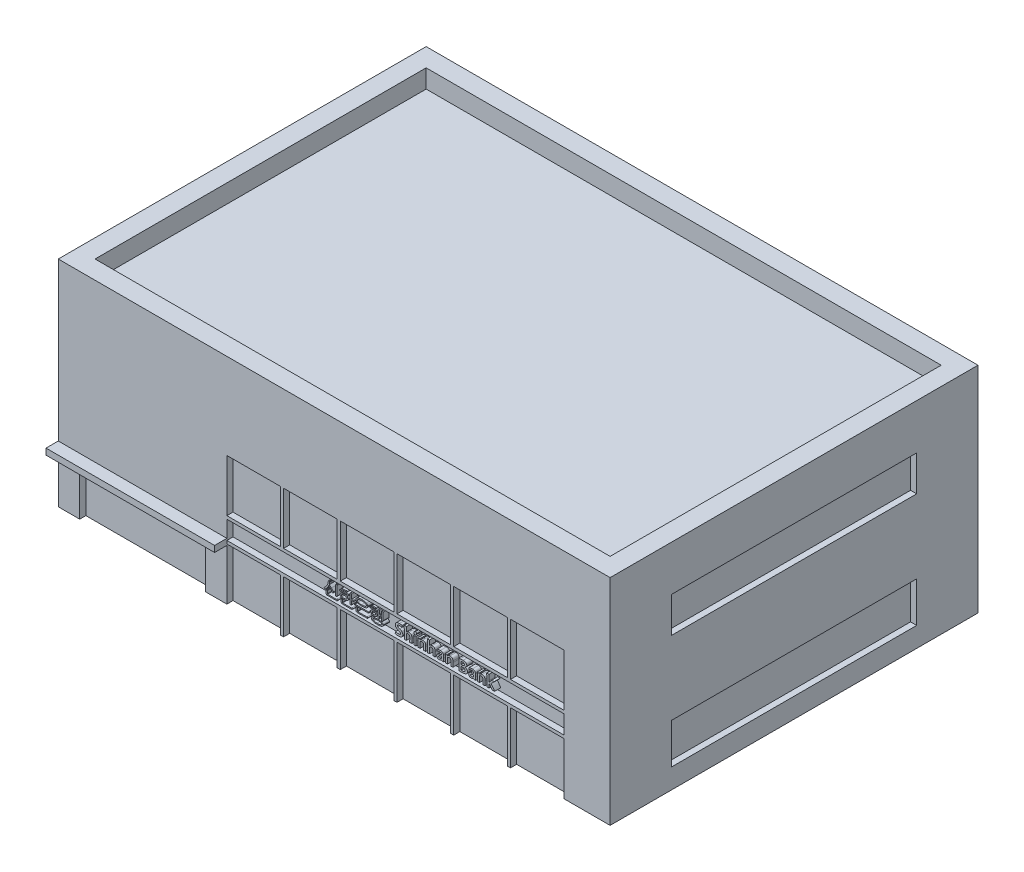
SolidWorks part; units mm, degrees
ref_plane "Front Plane" through (0, 0, 0) normal (0, 0, 1) x (1, 0, 0)
ref_plane "Top Plane" through (0, 0, 0) normal (0, 1, 0) x (1, 0, 0)
ref_plane "Right Plane" through (0, 0, 0) normal (1, 0, 0) x (0, 0, -1)
sketch "Sketch1" plane through (0, 0, 0) normal (0, 0, 1) x (1, 0, 0)
  line L1 (0, 0) -> (90, 0)
  line L2 (0, 0) -> (0, 35)
  line L3 (0, 35) -> (90, 35)
  line L4 (90, 0) -> (90, 35)
  dimension "D1" = 90
  dimension "D2" = 35
extrude "Boss-Extrude1" add sketch "Sketch1" along normal blind 60
sketch "Sketch2" plane through (0, 0, 60) normal (0, 0, 1) x (1, 0, 0)
  line L0 (0, 35) -> (0, 0) construction
  line L1 (0, 8.2944) -> (27.4975, 8.2944)
  line L2 (0, 8.2944) -> (0, 9.2944)
  line L3 (0, 9.2944) -> (27.4975, 9.2944)
  line L4 (27.4975, 8.2944) -> (27.4975, 9.2944)
  dimension "D1" = 1
extrude "Boss-Extrude2" add sketch "Sketch2" along normal blind 2
sketch "Sketch3" plane through (0, 0, 60) normal (0, 0, 1) x (1, 0, 0)
  line L0 (0, 8.2944) -> (27.4975, 8.2944) construction
  line L1 (3.5, 8.2944) -> (23.9975, 8.2944)
  line L2 (3.5, 8.2944) -> (3.5, 0)
  line L3 (3.5, 0) -> (23.9975, 0)
  line L4 (23.9975, 8.2944) -> (23.9975, 0)
  line L5 (0, 0) -> (90, 0) construction
  line L6 (0, 8.2944) -> (0, 0) construction
  line L7 (27.4975, 8.2944) -> (27.4975, 9.2944) construction
  line L8 (27.4975, 12) -> (82.4975, 12)
  line L9 (82.4975, 0) -> (27.4975, 0)
  line L10 (82.4975, 0) -> (82.4975, 21)
  line L11 (82.4975, 21) -> (27.4975, 21)
  line L12 (27.4975, 0) -> (27.4975, 21)
  line L13 (82.4975, 9) -> (27.4975, 9)
  line L14 (36.2475, 21) -> (36.2475, 12)
  line L15 (36.7475, 21) -> (36.7475, 12)
  line L16 (45.4975, 21) -> (45.4975, 12)
  line L17 (45.9975, 21) -> (45.9975, 12)
  line L18 (54.7475, 21) -> (54.7475, 12)
  line L19 (55.2475, 21) -> (55.2475, 12)
  line L20 (63.9975, 21) -> (63.9975, 12)
  line L21 (64.4975, 21) -> (64.4975, 12)
  line L22 (73.2475, 21) -> (73.2475, 12)
  line L23 (73.7475, 21) -> (73.7475, 12)
  line L24 (27.4975, 8.2944) -> (27.4975, 9.2944) construction
  line L25 (36.2475, 9) -> (36.2475, 0)
  line L26 (36.7475, 9) -> (36.7475, 0)
  line L27 (45.4975, 9) -> (45.4975, 0)
  line L28 (45.9975, 9) -> (45.9975, 0)
  line L29 (54.7475, 9) -> (54.7475, 0)
  line L30 (55.2475, 9) -> (55.2475, 0)
  line L31 (63.9975, 9) -> (63.9975, 0)
  line L32 (64.4975, 9) -> (64.4975, 0)
  line L33 (73.2475, 9) -> (73.2475, 0)
  line L34 (73.7475, 9) -> (73.7475, 0)
  line L35 (27.4975, 12.5) -> (82.4975, 12.5)
  line L36 (82.4975, 8.5) -> (27.4975, 8.5)
  line M22 (27.4975, 9.2944) -> (27.4975, 8.2944)
  line M23 (27.4975, 8.2944) -> (0, 8.2944)
  line M25 (0, 0) -> (90, 0)
  dimension "D1" = 3.5
  dimension "D2" = 3.5
  dimension "D3" = 55
  dimension "D4" = 0.5
  dimension "D5" = 0.5
  dimension "D6" = 0.5
  dimension "D7" = 0.5
  dimension "D8" = 0.5
  dimension "D9" = 8.75
  dimension "D10" = 8.75
  dimension "D11" = 8.75
  dimension "D12" = 8.75
  dimension "D13" = 8.75
  dimension "D14" = 3
  dimension "D15" = 9
  dimension "D16" = 9
  dimension "D17" = 0.5
  dimension "D18" = 0.5
extrude "Cut-Extrude1" cut sketch "Sketch3" against normal blind 1 contours L12 L35 L14 L11 | L15 L35 L16 L11 | L17 L35 L18 L11 | L19 L35 L20 L11 | L21 L35 L22 L11 | L23 L35 L10 L11 | L13 L10 L8 L12 M22 | L10 L36 L34 M25 | L33 L36 L32 M25 | L31 L36 L30 M25 | L29 L36 L28 M25 | L27 L36 L26 M25 | L25 L36 L12 M22 M25 | L4 L2 M23 M25
sketch "Sketch4" plane through (90, 0, 0) normal (1, 0, 0) x (0, 0, -1)
  line L1 (-50, 21.8297) -> (-10, 21.8297)
  line L2 (-50, 21.8297) -> (-50, 27.6186)
  line L3 (-50, 27.6186) -> (-10, 27.6186)
  line L4 (-10, 21.8297) -> (-10, 27.6186)
  line L5 (-50, 3.2449) -> (-10, 3.2449)
  line L6 (-50, 3.2449) -> (-50, 9.8297)
  line L7 (-50, 9.8297) -> (-10, 9.8297)
  line L8 (-10, 3.2449) -> (-10, 9.8297)
  line L9 (-60, 0) -> (-60, 35) construction
  line L10 (0, 0) -> (0, 35) construction
  dimension "D1" = 12
  dimension "D2" = 10
  dimension "D3" = 10
  dimension "D4" = 10
extrude "Cut-Extrude2" cut sketch "Sketch4" against normal blind 1
sketch "Sketch5" plane through (0, 0, 0) normal (0, -1, 0) x (1, 0, 0)
  line L0 (82.4975, 60) -> (73.7475, 60) construction
  line L1 (87, 3) -> (3, 3)
  line L2 (87, 3) -> (87, 57)
  line L3 (87, 57) -> (3, 57)
  line L4 (3, 3) -> (3, 57)
  line L5 (90, 60) -> (90, 0) construction
  line L6 (0, 0) -> (90, 0) construction
  line L7 (0, 60) -> (0, 0) construction
  dimension "D1" = 3
  dimension "D2" = 3
  dimension "D3" = 3
  dimension "D4" = 3
extrude "Cut-Extrude3" cut sketch "Sketch5" against normal offset from surface (29 mm away) 6 up to face at (45, 35, 30)
sketch "Sketch6" plane through (0, 35, 0) normal (0, 1, 0) x (1, 0, 0)
  line L0 (90, 0) -> (0, 0) construction
  line L1 (3, -3) -> (87, -3)
  line L2 (3, -3) -> (3, -57)
  line L3 (3, -57) -> (87, -57)
  line L4 (87, -3) -> (87, -57)
  line L5 (0, -60) -> (0, 0) construction
  line L6 (90, -60) -> (90, 0) construction
  line L7 (90, -60) -> (0, -60) construction
  dimension "D1" = 3
  dimension "D2" = 3
  dimension "D3" = 3
  dimension "D4" = 3
extrude "Cut-Extrude4" cut sketch "Sketch6" against normal blind 3
sketch "Sketch7" plane through (0, 0, 59) normal (0, 0, 1) x (1, 0, 0)
  text T0 "<b>신한은행   Shinhan Bank</b>" font "Candara" height 1.8
extrude "Boss-Extrude3" add sketch "Sketch7" along normal blind 1
